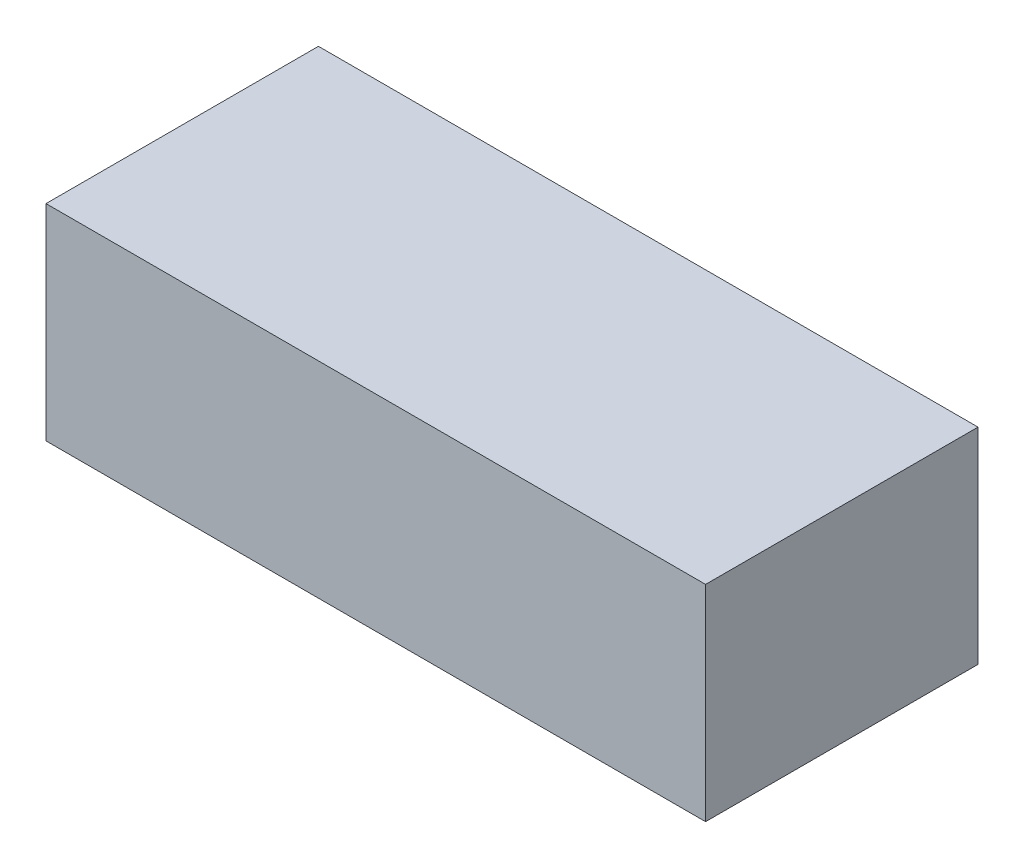
SolidWorks part; units mm, degrees
ref_plane "前视基准面" through (0, 0, 0) normal (0, 0, 1) x (1, 0, 0)
ref_plane "上视基准面" through (0, 0, 0) normal (0, 1, 0) x (1, 0, 0)
ref_plane "右视基准面" through (0, 0, 0) normal (1, 0, 0) x (0, 0, -1)
sketch "草图1" plane through (0, 0, 0) normal (0, 0, 1) x (1, 0, 0)
  line L1 (-69, 21.5) -> (69, 21.5)
  line L2 (-69, 21.5) -> (-69, -21.5)
  line L3 (-69, -21.5) -> (69, -21.5)
  line L4 (69, 21.5) -> (69, -21.5)
  line L5 (-69, 21.5) -> (69, -21.5) construction
  line L6 (-69, -21.5) -> (69, 21.5) construction
  point P0 (0, 0)
  dimension "D1" = 138
  dimension "D2" = 43
extrude "凸台-拉伸1" add sketch "草图1" along normal blind 57
